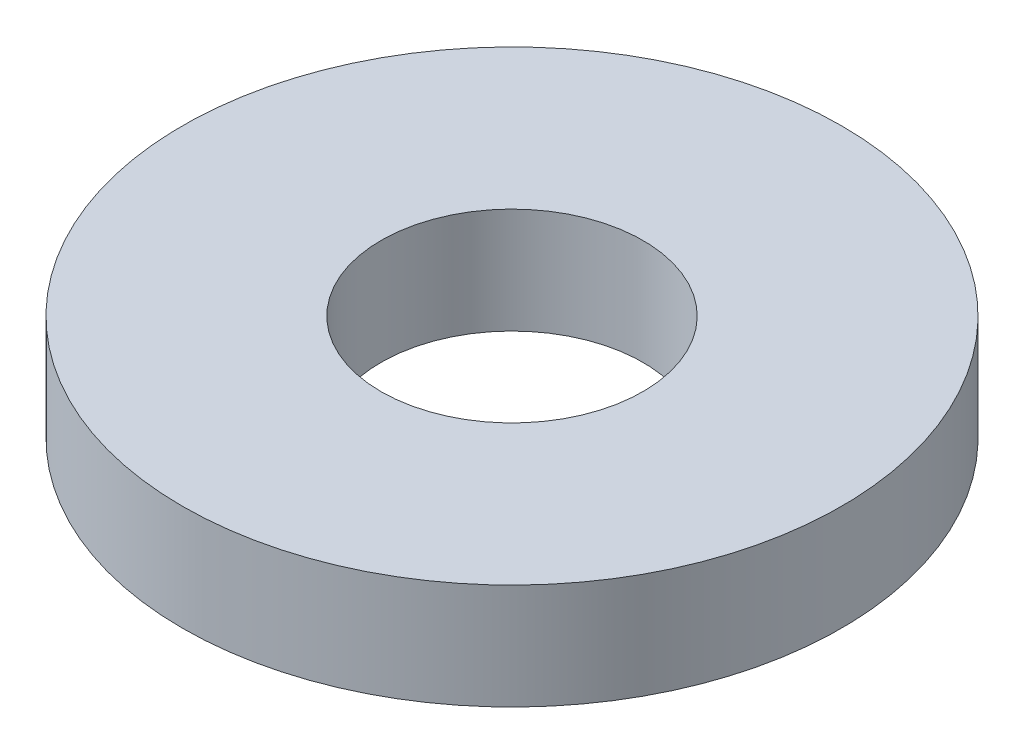
SolidWorks part; units mm, degrees
ref_plane "Front Plane" through (0, 0, 0) normal (0, 0, 1) x (1, 0, 0)
ref_plane "Top Plane" through (0, 0, 0) normal (0, 1, 0) x (1, 0, 0)
ref_plane "Right Plane" through (0, 0, 0) normal (1, 0, 0) x (0, 0, -1)
sketch "Sketch1" plane through (0, 0, 0) normal (0, 1, 0) x (1, 0, 0)
  circle A0 centre (0, 0) radius 0.7874
  circle A1 centre (0, 0) radius 1.9812
  dimension "D1" = 3.9624
  dimension "D2" = 1.5748
extrude "Boss-Extrude1" add sketch "Sketch1" along normal blind 0.635
